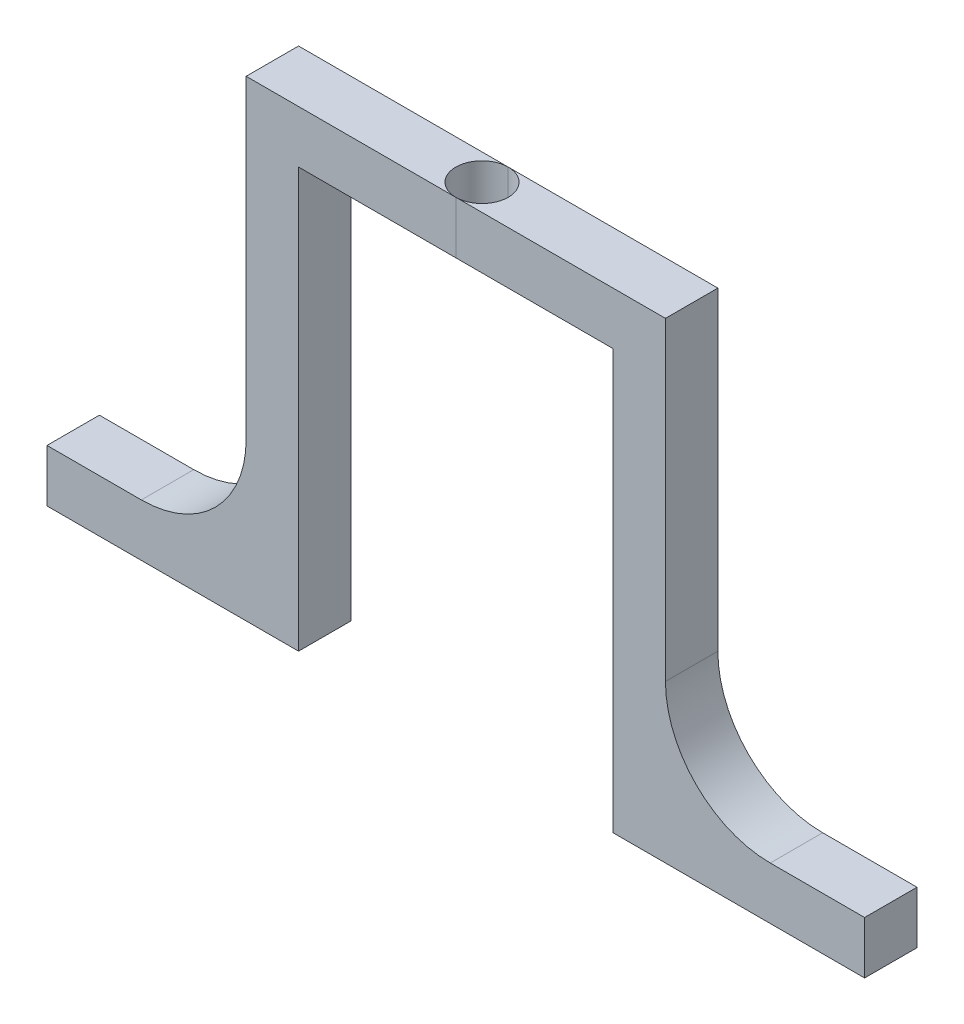
SolidWorks part; units mm, degrees
material "Hexcel AS4C (3000 Filaments)"
ref_plane "Front" through (0, 0, 0) normal (0, 0, 1) x (1, 0, 0)
ref_plane "Top" through (0, 0, 0) normal (0, 1, 0) x (1, 0, 0)
ref_plane "Right" through (0, 0, 0) normal (1, 0, 0) x (0, 0, -1)
sketch "Sketch1" plane through (0, 0, 0) normal (0, 0, 1) x (1, 0, 0)
  line L0 (0, 0) -> (24, 0)
  line L1 (24, 0) -> (24, 40)
  line L2 (24, 40) -> (39, 40)
  line L3 (39, 40) -> (39, -24.212) construction
  line L4 (0, 5) -> (19, 5)
  line L5 (19, 5) -> (19, 45)
  line L6 (19, 45) -> (39, 45)
  line L7 (0, 5) -> (0, 0)
  line L8 (78, 5) -> (78, 0)
  line L9 (59, 45) -> (39, 45)
  line L10 (59, 5) -> (59, 45)
  line L11 (78, 5) -> (59, 5)
  line L12 (54, 40) -> (39, 40)
  line L13 (54, 0) -> (54, 40)
  line L14 (78, 0) -> (54, 0)
  dimension "D2" = 24
  dimension "D3" = 40
  dimension "D4" = 90
  dimension "D1" = 15
  dimension "D5" = 5
extrude "Boss-Extrude1" add sketch "Sketch1" along normal blind 5
fillet "Fillet1" radius 10 2 edges at (19, 5, 2.5) (59, 5, 2.5)
sketch "Sketch2" plane through (0, 45, 0) normal (0, 1, 0) x (1, 0, 0)
  line L0 (45, 20.2764) -> (45, -20.2764) construction
  line L2 (19, -2.5) -> (59, -2.5) construction
  line L3 (19, -5) -> (19, 0) construction
  line L4 (59, -5) -> (59, 0) construction
  circle A0 centre (39, -2.5) radius 2.5
  point P3 (45, 0)
extrude "Cut-Extrude1" cut sketch "Sketch2" against normal up to surface (5 mm away) up to face at (39, 40, 2.5)
